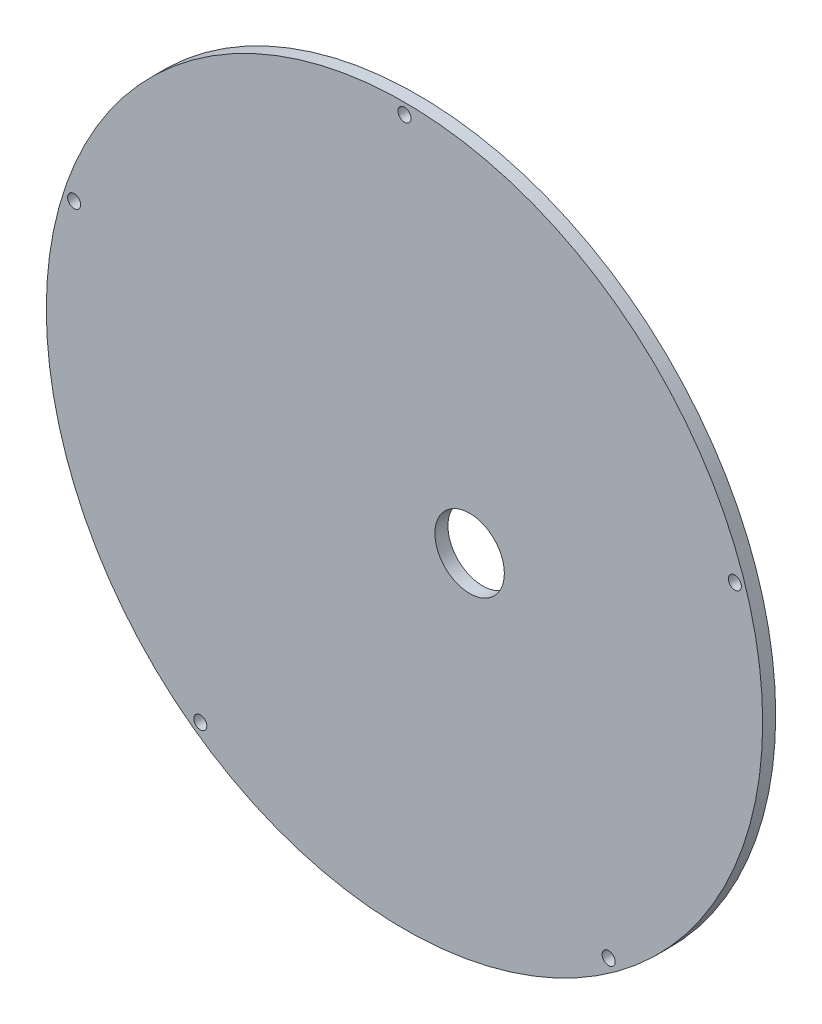
SolidWorks part; units mm, degrees
ref_plane "Front Plane" through (0, 0, 0) normal (0, 0, 1) x (1, 0, 0)
ref_plane "Top Plane" through (0, 0, 0) normal (0, 1, 0) x (1, 0, 0)
ref_plane "Right Plane" through (0, 0, 0) normal (1, 0, 0) x (0, 0, -1)
sketch "Sketch1" plane through (0, 0, 0) normal (0, 0, 1) x (1, 0, 0)
  circle A0 centre (0, 0) radius 82.5
  dimension "D1" = 165
extrude "Boss-Extrude1" add sketch "Sketch1" along normal blind 3
sketch "Sketch2" plane through (0, 0, 3) normal (0, 0, 1) x (1, 0, 0)
  line L0 (0, 82.5) -> (0, 80) construction
  circle A0 centre (0, 0) radius 82.5 construction
  dimension "D1" = 80
hole_wizard "Ø3.0mm Dowel Hole1" positions "3DSketch1" profile "Sketch3" hole size "Ø3.0" standard "ISO" end condition through all
sketch3d "3DSketch1"
  point P0 (0, 80, 3)
sketch "Sketch3" plane through (0, 80, 3) normal (1, 0, 0) x (0, -1, 0)
  line L0 (0, 0) -> (0, 3)
  line L1 (0, 3) -> (1.5, 3)
  line L2 (1.5, 3) -> (1.5, 0)
  line L5 (1.5, 0) -> (0, 0)
  line L11 (0, -6.35) -> (0, 107.95) construction
  dimension "Thru Hole Dia." = 3
  dimension "Thru Hole Depth" = 3
pattern_circular "CirPattern1" count 5 over 360 about axis through (0, 0, 0) along (0, 0, 1) of "Ø3.0mm Dowel Hole1"
sketch "Sketch4" plane through (0, 0, 3) normal (0, 0, 1) x (1, 0, 0)
  line L0 (0, 0) -> (15, 0) construction
  circle A0 centre (15, 0) radius 8
  dimension "D1" = 16
  dimension "D2" = 15
extrude "Cut-Extrude1" cut sketch "Sketch4" against normal through all
